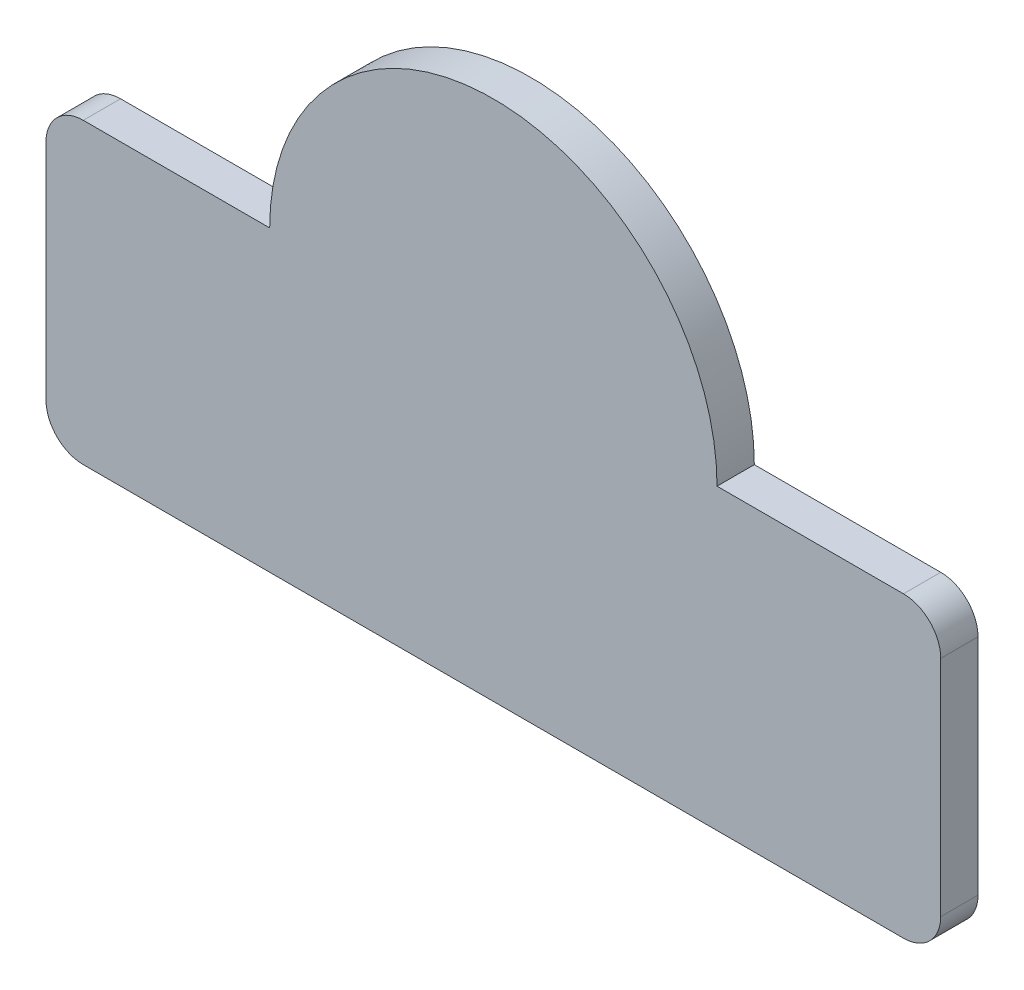
SolidWorks part; units mm, degrees
other "Camera1"
other "Camera2"
ref_plane "Front Plane" through (0, 0, 0) normal (0, 0, 1) x (1, 0, 0)
ref_plane "Top Plane" through (0, 0, 0) normal (0, 1, 0) x (1, 0, 0)
ref_plane "Right Plane" through (0, 0, 0) normal (1, 0, 0) x (0, 0, -1)
sketch "Sketch1" plane through (0, 0, 0) normal (0, 0, 1) x (1, 0, 0)
  line L0 (6.9108, 13.8216) -> (34.554, 13.8216) construction
  line L1 (6.9108, 13.8216) -> (34.554, 13.8216) construction
  line L2 (35.7853, 16.1395) -> (54.8353, 16.1395)
  line L3 (-21.3647, -9.2605) -> (54.8353, -9.2605)
  line L4 (-21.3647, -9.2605) -> (-21.3647, 16.1395)
  line L5 (-21.3647, 16.1395) -> (-2.3147, 16.1395)
  line L6 (54.8353, -9.2605) -> (54.8353, 16.1395)
  arc A0 (35.7853, 16.1395) -> (-2.3147, 16.1395) centre (16.7353, 16.1395) ccw
  point P10 (16.7353, -9.2605)
  dimension "D1" = 19.05
  dimension "D2" = 25.4
  dimension "D3" = 76.2
extrude "Boss-Extrude3" add sketch "Sketch1" along normal blind 3.175
fillet "Fillet1" radius 3.175 4 edges at (54.8353, 16.1395, 1.5875) (54.8353, -9.2605, 1.5875) (-21.3647, -9.2605, 1.5875) (-21.3647, 16.1395, 1.5875)
sketch "Sketch15" plane through (0, 0, 0) normal (0, 0, 1) x (1, 0, 0)
  line L0 (-21.3647, -6.0855) -> (54.8353, -6.0855)
